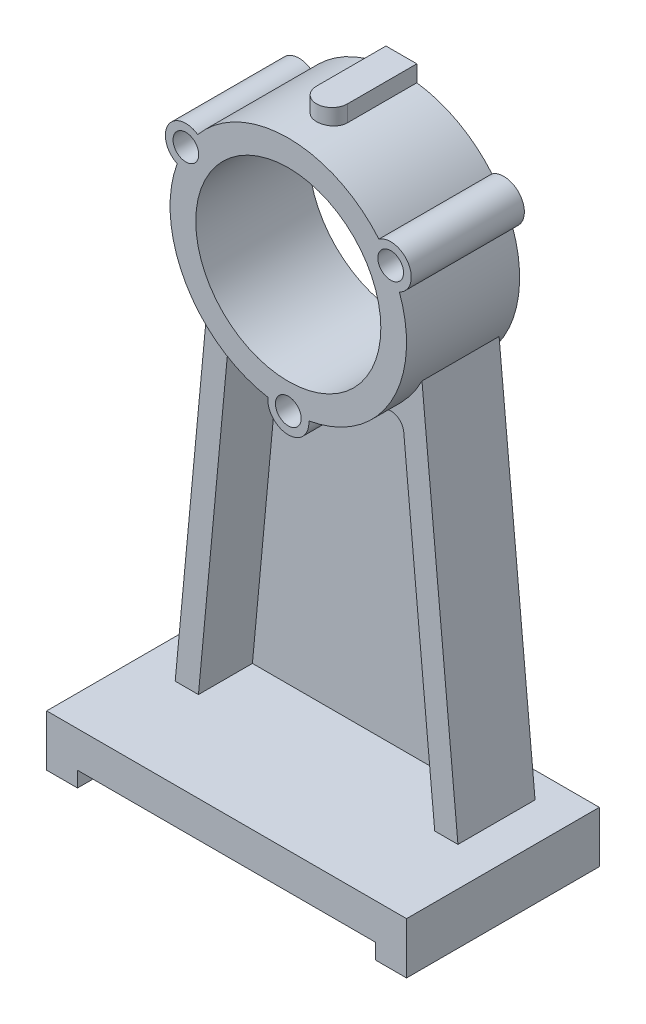
SolidWorks part; units mm, degrees
ref_plane "前视基准面" through (0, 0, 0) normal (0, 0, 1) x (1, 0, 0)
ref_plane "上视基准面" through (0, 0, 0) normal (0, 1, 0) x (1, 0, 0)
ref_plane "右视基准面" through (0, 0, 0) normal (1, 0, 0) x (0, 0, -1)
other "Configuration Table"
sketch "草图1" plane through (0, 0, 0) normal (0, 0, 1) x (1, 0, 0)
  line L0 (0, 74.3326) -> (0, 46) construction
  line L1 (0, -46) -> (0, -79.7246) construction
  arc A0 (7.9697, -45.3043) -> (43.2196, 15.7502) centre (0, 0) ccw
  arc A1 (-7.9697, -45.3043) -> (7.9697, -45.3043) centre (0, -46) ccw
  arc A2 (-35.2499, 29.5541) -> (-43.2196, 15.7502) centre (-39.8372, 23) ccw
  arc A3 (43.2196, 15.7502) -> (35.2499, 29.5541) centre (39.8372, 23) ccw
  arc A4 (35.2499, 29.5541) -> (-35.2499, 29.5541) centre (0, 0) ccw
  arc A5 (-43.2196, 15.7502) -> (-7.9697, -45.3043) centre (0, 0) ccw
  point P14 (0, 0)
  dimension "D1" = 92
  dimension "D2" = 16
  dimension "D3" = 3
extrude "凸台-拉伸1" add sketch "草图1" along normal blind 44
sketch "草图2" plane through (0, 0, 0) normal (1, 0, 0) x (0, 0, -1)
  line L0 (0, -45.3043) -> (0, 15.7502) construction
  line L1 (-68, -170) -> (7, -170)
  line L2 (-68, -170) -> (-68, -190)
  line L3 (-68, -190) -> (7, -190)
  line L4 (7, -170) -> (7, -190)
  line L5 (-68, -170) -> (7, -190) construction
  line L6 (-68, -190) -> (7, -170) construction
  point P0 (-30.5, -180)
  point P5 (-21.9695, -91.8862)
  dimension "D1" = 75
  dimension "D2" = 20
  dimension "D3" = 7
  dimension "D4" = 170
extrude "凸台-拉伸2" add sketch "草图2" along normal mid plane 140 separate body
ref_plane "基准面1" through (0, 0, 3) normal (0, 0, 1) x (1, 0, 0)
sketch "草图3" plane through (0, 0, 3) normal (0, 0, 1) x (1, 0, 0)
  line L0 (0, 98.2938) -> (0, -241.2633) construction
  line L1 (70, -170) -> (-70, -170) construction
  line L2 (55, -170) -> (45.9604, -170)
  line L3 (-33.9018, -41.5377) -> (-45.9604, -170)
  line L4 (-41, -20.8567) -> (-55, -170)
  line L5 (-38.9426, 1.061) -> (-54.3265, -162.8251) construction
  line L6 (-29.982, 0.2199) -> (-45.3659, -163.6662) construction
  line L7 (33.9018, -41.5377) -> (45.9604, -170)
  line L8 (41, -20.8567) -> (55, -170)
  line L9 (-45.9604, -170) -> (-55, -170)
  arc A0 (-43.2196, 15.7502) -> (-7.9697, -45.3043) centre (0, 0) ccw construction
  arc A1 (7.9697, -45.3043) -> (43.2196, 15.7502) centre (0, 0) ccw construction
  arc A2 (-41, -20.8567) -> (-26.088, -37.8869) centre (0, 0) ccw
  arc A3 (26.088, -37.8869) -> (41, -20.8567) centre (0, 0) ccw
  arc A4 (-26.088, -37.8869) -> (-33.9018, -41.5377) centre (-28.9236, -42.005) ccw
  arc A5 (26.088, -37.8869) -> (33.9018, -41.5377) centre (28.9236, -42.005) cw
  dimension "D2" = 10
  dimension "D3" = 82
  dimension "D4" = 110
  dimension "D1" = 9
extrude "凸台-拉伸3" add sketch "草图3" along normal blind 30
sketch "草图4" plane through (0, 0, 0) normal (1, 0, 0) x (0, 0, -1)
  line L0 (7, -170) -> (-68, -170) construction
  line L1 (-12, -170) -> (-3, -170)
  line L2 (-12, -170) -> (-12, 0)
  line L3 (-12, 0) -> (-3, 0)
  line L4 (-3, -170) -> (-3, 0)
  line L5 (-12, -170) -> (-3, 0) construction
  line L6 (-12, 0) -> (-3, -170) construction
  line L7 (-3, 77) -> (-3, -77) construction
  point P0 (-7.5, -85)
  dimension "D1" = 9
extrude "凸台-拉伸4" add sketch "草图4" along normal up to next and the other way up to next
sketch "草图5" plane through (0, 0, 0) normal (0, 1, 0) x (1, 0, 0)
  line L0 (0, 27.6465) -> (0, -93.2482) construction
  line L1 (35.2499, 0) -> (-35.2499, 0) construction
  line L3 (-6, -27) -> (-6, 0)
  line L4 (-6, 0) -> (6, 0)
  line L5 (6, -27) -> (6, 0)
  line L6 (-4.0206, -22.5464) -> (6, 0) construction
  line L7 (-6, 0) -> (0, -13.5) construction
  arc A0 (-6, -27) -> (6, -27) centre (0, -27) ccw
  point P2 (0, -13.5)
  dimension "D2" = 12
  dimension "D1" = 27
extrude "凸台-拉伸5" add sketch "草图5" along normal blind 52
sketch "草图6" plane through (0, 0, 0) normal (0, 0, 1) x (1, 0, 0)
  line L0 (0, 90.082) -> (0, -207.8056) construction
  line L1 (70, -170) -> (70, -190) construction
  line L2 (-58, -184) -> (58, -184)
  line L3 (-58, -184) -> (-58, -190)
  line L4 (-58, -190) -> (58, -190)
  line L5 (58, -184) -> (58, -190)
  line L6 (-58, -184) -> (58, -190) construction
  line L7 (-58, -190) -> (58, -184) construction
  line L8 (70, -190) -> (-70, -190) construction
  circle A0 centre (0, 0) radius 36
  circle A1 centre (0, -46) radius 5
  arc A2 (-7.9697, -45.3043) -> (7.9697, -45.3043) centre (0, -46) ccw construction
  circle A3 centre (-39.8372, 23) radius 5
  circle A4 centre (39.8372, 23) radius 5
  point P12 (0, -187)
  point P18 (0, 0)
  dimension "D1" = 72
  dimension "D2" = 10
  dimension "D4" = 6
  dimension "D5" = 12
  dimension "D3" = 3
extrude "切除-拉伸1" cut sketch "草图6" against normal through all both and the other way through all
